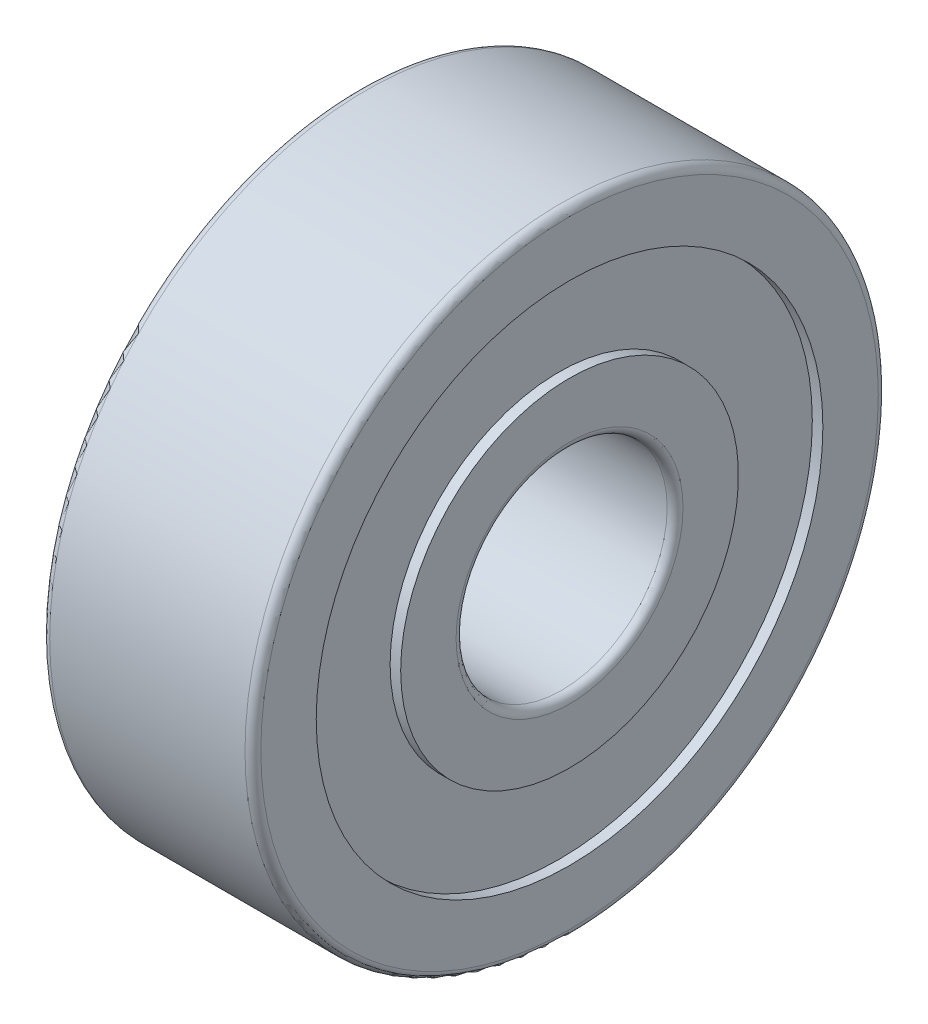
SolidWorks part; units mm, degrees
material "不锈钢 (铁素体)"
ref_plane "前视基准面" through (0, 0, 0) normal (0, 0, 1) x (1, 0, 0)
ref_plane "上视基准面" through (0, 0, 0) normal (0, 1, 0) x (1, 0, 0)
ref_plane "右视基准面" through (0, 0, 0) normal (1, 0, 0) x (0, 0, -1)
sketch "草图1" plane through (0, 0, 0) normal (0, 0, 1) x (1, 0, 0)
  line L0 (0, 0) -> (47.6548, 0) construction
  line L1 (0, 0) -> (0, 12) construction
  line L2 (-4, 12) -> (4, 12)
  line L3 (4, 12) -> (4, 9.6)
  line L4 (4, 9.6) -> (3.6, 9.6)
  line L5 (3.6, 9.6) -> (3.6, 6.4)
  line L6 (3.6, 6.4) -> (4, 6.4)
  line L7 (4, 6.4) -> (4, 4)
  line L8 (4, 4) -> (-4, 4)
  line L9 (-4, 6.4) -> (-4, 4)
  line L10 (-3.6, 6.4) -> (-4, 6.4)
  line L11 (-3.6, 9.6) -> (-3.6, 6.4)
  line L12 (-4, 9.6) -> (-3.6, 9.6)
  line L13 (-4, 12) -> (-4, 9.6)
  dimension "d_inner" = 8
  dimension "D_outer" = 24
  dimension "d2" = 12.8
  dimension "D3" = 19.2
  dimension "B" = 8
  dimension "D5" = 0.4
revolve "旋转1" add sketch "草图1" angle 360 about L0
fillet "圆角1" radius 0.3 4 edges at (-4, 0, 12) (4, 0, 12) (-4, 0, 4) (4, 0, 4)
equation "\"D5@草图1\" = 0.05 * \"B@草图1\""
